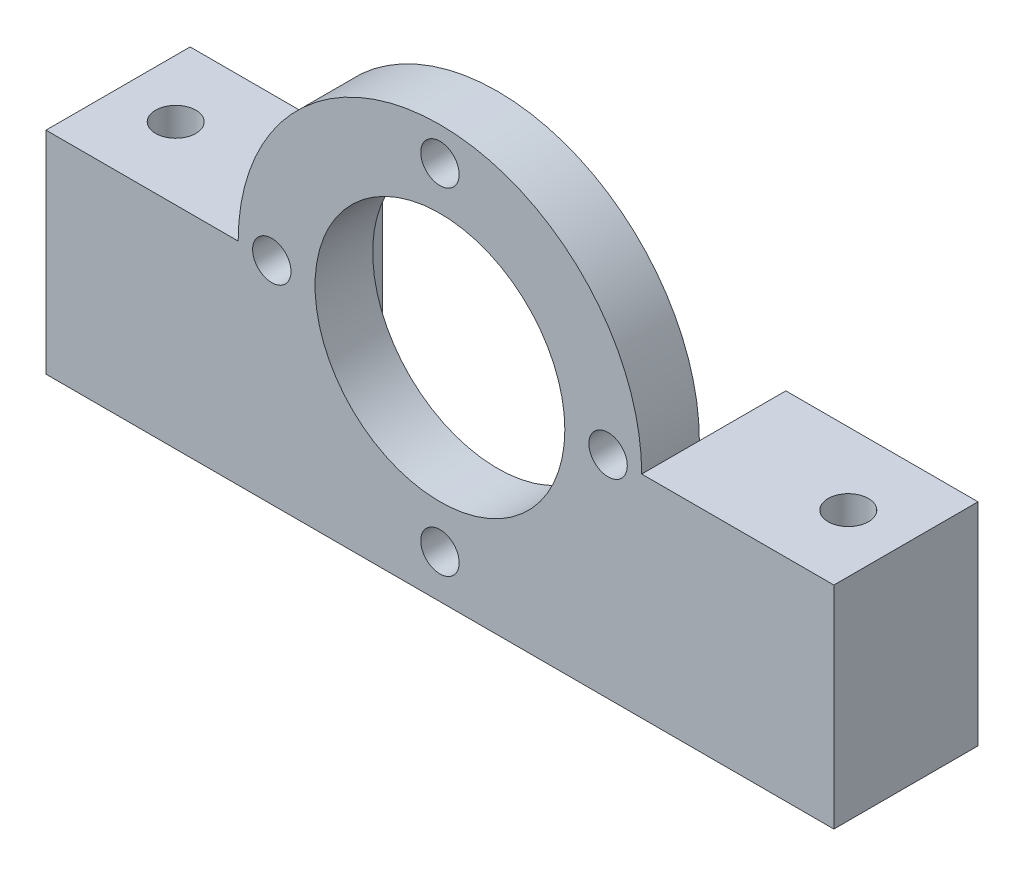
SolidWorks part; units mm, degrees
material "6061 合金"
ref_plane "前视基准面" through (0, 0, 0) normal (0, 0, 1) x (1, 0, 0)
ref_plane "上视基准面" through (0, 0, 0) normal (0, 1, 0) x (1, 0, 0)
ref_plane "右视基准面" through (0, 0, 0) normal (1, 0, 0) x (0, 0, -1)
sketch "草图1" plane through (0, 0, 0) normal (0, 0, 1) x (1, 0, 0)
  line L0 (0, 0) -> (0, 76.2204) construction
  line L1 (-21, 22) -> (-21, 0)
  line L2 (-21, 0) -> (21, 0)
  line L3 (21, 0) -> (21, 22)
  arc A0 (21, 22) -> (-21, 22) centre (0, 22) ccw
  circle A1 centre (0, 22) radius 13
  circle A2 centre (0, 22) radius 17.5 construction
  circle A3 centre (0, 39.5) radius 2
  circle A4 centre (17.5, 22) radius 2
  circle A5 centre (0, 4.5) radius 2
  circle A6 centre (-17.5, 22) radius 2
  dimension "D1" = 42
  dimension "D3" = 26
  dimension "D4" = 35
  dimension "D5" = 4
  dimension "D2" = 22
extrude "凸台-拉伸1" add sketch "草图1" along normal blind 6
sketch "草图2" plane through (0, 0, 6) normal (0, 0, 1) x (1, 0, 0)
  line L0 (0, 0) -> (0, -50000) construction
  line L1 (-41, 22) -> (-21, 22)
  line L2 (-41, 22) -> (-41, 0)
  line L3 (-41, 0) -> (-21, 0)
  line L4 (-21, 22) -> (-21, 0)
  line L5 (-41, 22) -> (-21, 0) construction
  line L6 (-41, 0) -> (-21, 22) construction
  line L7 (41, 0) -> (21, 0)
  line L8 (21, 22) -> (21, 0)
  line L9 (41, 22) -> (21, 22)
  line L10 (41, 22) -> (41, 0)
  point P0 (-31, 11)
  dimension "D1" = 20
extrude "凸台-拉伸2" add sketch "草图2" against normal blind 15
sketch "草图3" plane through (0, 22, 0) normal (0, 1, 0) x (1, 0, 0)
  line L0 (-41, 1.5) -> (49959, 1.5) construction
  line L2 (-21, -6) -> (-41, -6) construction
  line L3 (0, 0) -> (0, -50000) construction
  line L4 (-41, 9) -> (-41, -6) construction
  circle A0 centre (-35, 1.5) radius 2.1
  circle A1 centre (35, 1.5) radius 2.1
  dimension "D2" = 6
  dimension "D3" = 4.2
  dimension "D1" = 7.5
extrude "切除-拉伸1" cut sketch "草图3" against normal through all
